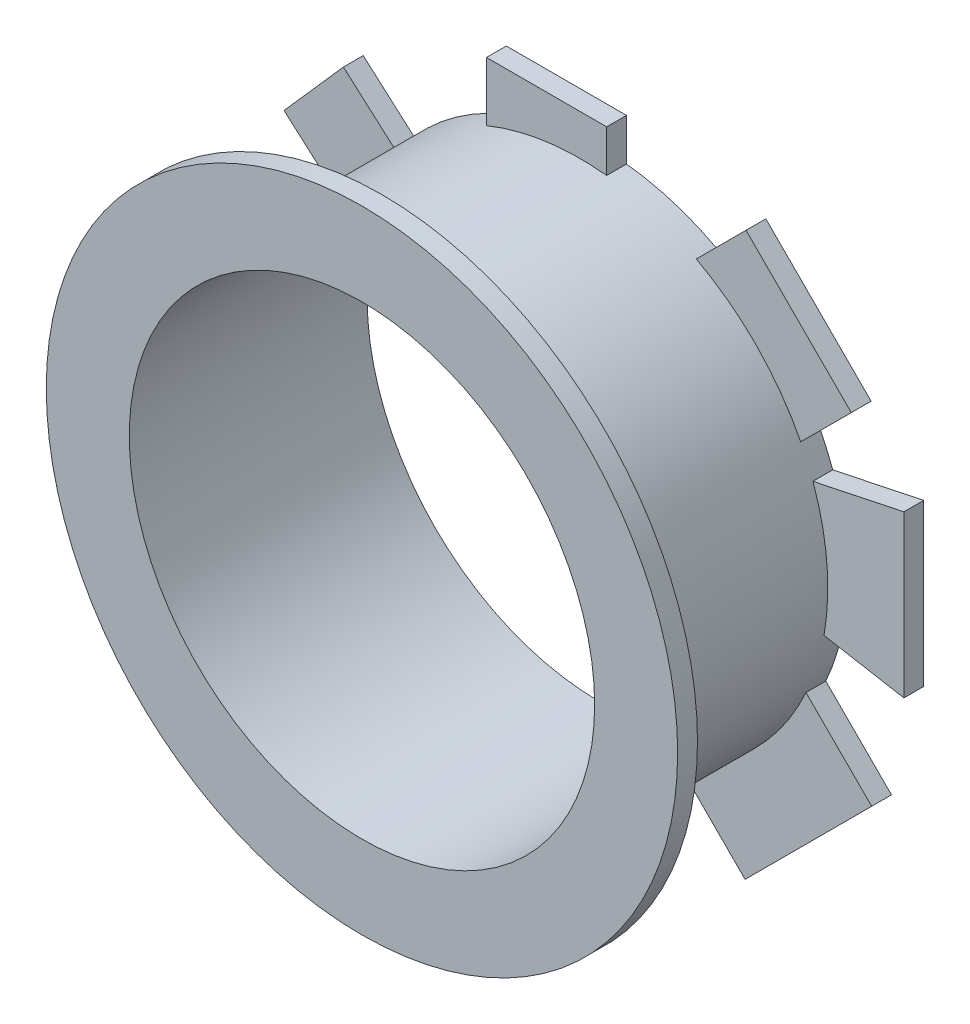
SolidWorks part; units mm, degrees
ref_plane "Přední rovina" through (0, 0, 0) normal (0, 0, 1) x (1, 0, 0)
ref_plane "Horní rovina" through (0, 0, 0) normal (0, 1, 0) x (1, 0, 0)
ref_plane "Pravá rovina" through (0, 0, 0) normal (1, 0, 0) x (0, 0, -1)
sketch "Skica1" plane through (0, 0, 0) normal (0, 0, 1) x (1, 0, 0)
  circle A1 centre (0, 0) radius 1.25
  dimension "D2" = 2.5
extrude "Přidat vysunutím1" add sketch "Skica1" along normal blind 1
sketch "Skica2" plane through (0, 0, 1) normal (0, 0, 1) x (1, 0, 0)
  circle A0 centre (0, 0) radius 1.1738
extrude "Odebrat vysunutím1" cut sketch "Skica2" against normal blind 10
ref_plane "Rovina1" through (0, 0, 1) normal (0, 0, 1) x (1, 0, 0)
sketch "Skica3" plane through (0, 0, 1) normal (0, 0, 1) x (1, 0, 0)
  circle A0 centre (0, 0) radius 1.5925
  circle A1 centre (0, 0) radius 1.1738
extrude "Přidat vysunutím2" add sketch "Skica3" along normal blind 0.1
ref_plane "Rovina2" through (0, 0, 0) normal (0, 0, -1) x (-1, 0, 0)
sketch "Skica4" plane through (0, 0, 0) normal (0, 0, -1) x (-1, 0, 0)
  line L0 (-0.1343, 1.2428) -> (-0.1343, 1.4554)
  line L1 (-0.1343, 1.4554) -> (0.4719, 1.4554)
  line L2 (0.4719, 1.4554) -> (0.4719, 1.1575)
  line L3 (0.9375, 0.8268) -> (1.1936, 1.0527)
  line L4 (1.1936, 1.0527) -> (1.4931, 0.7131)
  line L5 (1.4931, 0.7131) -> (1.1733, 0.4311)
  line L6 (-0.5863, 1.104) -> (-0.8374, 1.355)
  line L7 (-0.8374, 1.355) -> (-1.3685, 0.8239)
  line L8 (-1.3685, 0.8239) -> (-1.1132, 0.5686)
  line L9 (-0.4968, -1.147) -> (-0.8328, -1.483)
  line L10 (-0.8328, -1.483) -> (-1.4712, -0.8446)
  line L11 (-1.4712, -0.8446) -> (-1.1398, -0.5132)
  line L12 (0.8927, -0.8749) -> (1.1889, -1.1652)
  line L13 (1.1889, -1.1652) -> (1.5225, -0.8248)
  line L14 (1.5214, -0.7117) -> (1.1889, -0.3859)
  line L15 (-1.2308, -0.2184) -> (-1.6339, -0.2899)
  line L16 (-1.6339, -0.2899) -> (-1.6339, 0.5233)
  line L17 (-1.6339, 0.5233) -> (-1.1748, 0.4271)
  line L18 (1.245, 0.1118) -> (1.3752, 0.0917)
  line L19 (1.3752, 0.0917) -> (1.3752, 0)
  line L20 (1.3752, 0) -> (1.25, 0)
  line L21 (-0.133, -1.2429) -> (-0.0957, -1.483)
  line L22 (-0.0957, -1.483) -> (0.5544, -1.4277)
  line L23 (0.5544, -1.4277) -> (0.4525, -1.1652)
  circle A0 centre (0, 0) radius 1.1738
  arc A1 (-0.1343, 1.2428) -> (-0.5863, 1.104) centre (0, 0) ccw
  arc A2 (0.9375, 0.8268) -> (0.4719, 1.1575) centre (0, 0) ccw
  arc A3 (-1.1132, 0.5686) -> (-1.1748, 0.4271) centre (0, 0) ccw
  arc A4 (-0.4968, -1.147) -> (-0.133, -1.2429) centre (0, 0) ccw
  arc A5 (1.1889, -0.3859) -> (1.25, 0) centre (0, 0) ccw
  arc A6 (-1.2308, -0.2184) -> (-1.1398, -0.5132) centre (0, 0) ccw
  arc A7 (0.4525, -1.1652) -> (0.8927, -0.8749) centre (0, 0) ccw
  arc A8 (1.245, 0.1118) -> (1.1733, 0.4311) centre (0, 0) ccw
  circle A9 centre (0, 0) radius 1.25 construction
  arc A10 (1.5225, -0.8248) -> (1.5214, -0.7117) centre (1.4654, -0.7688) ccw
  dimension "D1" = 0.08
extrude "Přidat vysunutím3" add sketch "Skica4" along normal blind 0.1
